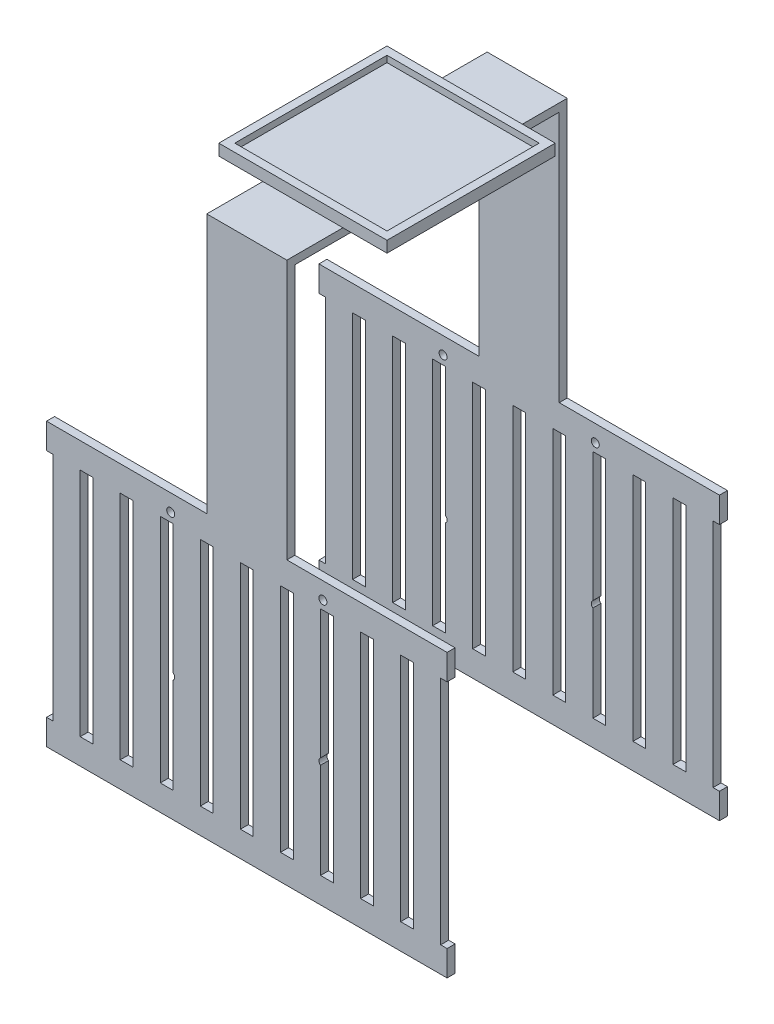
SolidWorks part; units mm, degrees
ref_plane "Plan de face" through (0, 0, 0) normal (0, 0, 1) x (1, 0, 0)
ref_plane "Plan de dessus" through (0, 0, 0) normal (0, 1, 0) x (1, 0, 0)
ref_plane "Plan de droite" through (0, 0, 0) normal (1, 0, 0) x (0, 0, -1)
sketch "Esquisse1" plane through (0, 0, 0) normal (0, 0, 1) x (1, 0, 0)
  line L0 (-62.5, 77.5) -> (62.5, 77.5) construction
  line L2 (-62.5, 88) -> (-62.5, -88)
  line L3 (-62.5, -88) -> (62.5, -88)
  line L4 (62.5, 88) -> (62.5, -88)
  line L5 (-62.5, 88) -> (62.5, -88) construction
  line L6 (-62.5, -88) -> (62.5, 88) construction
  line L7 (-62.5, -10.5) -> (62.5, -10.5) construction
  line L8 (0, 86.5) -> (0, -88) construction
  line L9 (-62.5, 88) -> (-25, 88)
  line L10 (-25, 88) -> (-25, 250.03)
  line L11 (-25, 250.03) -> (25, 250.03)
  line L12 (62.5, 88) -> (25, 88)
  line L13 (25, 88) -> (25, 250.03)
  circle A0 centre (-47.5, 77.5) radius 2.5
  circle A1 centre (-47.5, -10.5) radius 2.5
  circle A2 centre (47.5, -10.5) radius 2.5
  circle A3 centre (47.5, 77.5) radius 2.5
  point P0 (0, 0)
  point P28 (0, 250.03)
  dimension "D5" = 5
  dimension "D6" = 5
  dimension "D1" = 125
  dimension "D2" = 176
  dimension "D3" = 77.5
  dimension "D4" = 88
  dimension "D7" = 15
  dimension "D8" = 15
  dimension "D9" = 338.03
  dimension "D10" = 50
extrude "Boss.-Extru.1" add sketch "Esquisse1" along normal blind 5
sketch "Esquisse2" plane through (0, 250.03, 0) normal (0, 1, 0) x (1, 0, 0)
  line L1 (-25, -5) -> (25, -5)
  line L2 (-25, -5) -> (-25, 170)
  line L3 (-25, 170) -> (25, 170)
  line L4 (25, -5) -> (25, 170)
  dimension "D1" = 175
extrude "Boss.-Extru.2" add sketch "Esquisse2" against normal blind 5
sketch "Esquisse3" plane through (0, 0, -170) normal (0, 0, -1) x (-1, 0, 0)
  line L8 (25, 88) -> (25, 250.03)
  line L9 (25, 250.03) -> (-25, 250.03)
  line L10 (-25, 250.03) -> (-25, 88)
  line L11 (-25, 88) -> (-62.5, 88)
  line L12 (-62.5, 88) -> (-62.5, -88)
  line L13 (-62.5, -88) -> (62.5, -88)
  line L14 (62.5, -88) -> (62.5, 88)
  line L15 (62.5, 88) -> (25, 88)
  line L16 (25, 88) -> (25, 250.03)
  line L17 (25, 250.03) -> (-25, 250.03)
  line L18 (-25, 250.03) -> (-25, 88)
  line L19 (-25, 88) -> (-62.5, 88)
  line L20 (-62.5, 88) -> (-62.5, -88)
  line L21 (-62.5, -88) -> (62.5, -88)
  line L22 (62.5, -88) -> (62.5, 88)
  line L23 (62.5, 88) -> (25, 88)
  circle A1 centre (47.5, -10.5) radius 2.5
  circle A2 centre (47.5, -10.5) radius 2.5
  circle A3 centre (47.5, 77.5) radius 2.5
  circle A4 centre (47.5, 77.5) radius 2.5
  circle A5 centre (-47.5, 77.5) radius 2.5
  circle A6 centre (-47.5, 77.5) radius 2.5
  circle A7 centre (-47.5, -10.5) radius 2.5
  circle A8 centre (-47.5, -10.5) radius 2.5
  dimension "D1" = 0
  dimension "D2" = 0
  dimension "D3" = 0
  dimension "D4" = 0
  dimension "D5" = 0
extrude "Boss.-Extru.3" add sketch "Esquisse3" against normal blind 5
sketch "Esquisse4" plane through (0, 250.03, 0) normal (0, 1, 0) x (1, 0, 0)
  line L0 (-25, 82.5) -> (25, 82.5) construction
  line L1 (-25, -5) -> (-25, 170) construction
  line L2 (25, -5) -> (25, 170) construction
  line L3 (0, 170) -> (0, -5) construction
  line L4 (25, 170) -> (-25, 170) construction
  line L5 (25, -5) -> (-25, -5) construction
  line L7 (-52.5, 135) -> (52.5, 135)
  line L8 (-52.5, 135) -> (-52.5, 30)
  line L9 (-52.5, 30) -> (52.5, 30)
  line L10 (52.5, 135) -> (52.5, 30)
  line L11 (-52.5, 135) -> (52.5, 30) construction
  line L12 (-52.5, 30) -> (52.5, 135) construction
  point P12 (0, 82.5)
  dimension "D1" = 105
  dimension "D2" = 105
extrude "Boss.-Extru.4" add sketch "Esquisse4" along normal blind 3
sketch "Esquisse5" plane through (0, 253.03, 0) normal (0, 1, 0) x (1, 0, 0)
  line L0 (47.5, 130) -> (-47.5, 130)
  line L1 (-47.5, 130) -> (-47.5, 35)
  line L2 (-47.5, 35) -> (47.5, 35)
  line L3 (47.5, 35) -> (47.5, 130)
  line L4 (52.5, 30) -> (52.5, 135)
  line L5 (52.5, 135) -> (-52.5, 135)
  line L6 (-52.5, 135) -> (-52.5, 30)
  line L7 (-52.5, 30) -> (52.5, 30)
  line L8 (52.5, 30) -> (52.5, 135)
  line L9 (52.5, 135) -> (-52.5, 135)
  line L10 (-52.5, 135) -> (-52.5, 30)
  line L11 (-52.5, 30) -> (52.5, 30)
  dimension "D1" = 0
  dimension "D2" = 5
extrude "Boss.-Extru.5" add sketch "Esquisse5" along normal blind 4
sketch "Esquisse6" plane through (0, 0, -170) normal (0, 0, -1) x (-1, 0, 0)
  line L0 (-25, 88) -> (-62.5, 88) construction
  line L1 (-125, -88) -> (125, -88)
  line L2 (-125, -88) -> (-125, 88)
  line L3 (-125, 88) -> (125, 88)
  line L4 (125, -88) -> (125, 88)
  line L5 (-125, -88) -> (125, 88) construction
  line L6 (-125, 88) -> (125, -88) construction
  circle A0 centre (-47.5, 77.5) radius 2.5
  circle A1 centre (47.5, 77.5) radius 2.5023
  circle A2 centre (-47.5, -10.5) radius 2.6964
  circle A3 centre (47.5, -10.5) radius 2.6964
  point P0 (0, 0)
  dimension "D1" = 250
extrude "Boss.-Extru.6" add sketch "Esquisse6" against normal up to surface (5 mm away) up to face at (45, -10.5, -165)
sketch "Esquisse8" plane through (0, 0, 5) normal (0, 0, 1) x (1, 0, 0)
  line L4 (-125, -88) -> (125, -88)
  line L5 (-125, 88) -> (-125, -88)
  line L6 (125, 88) -> (-125, 88)
  line L7 (125, -88) -> (125, 88)
  line L8 (-125, -88) -> (125, -88)
  line L9 (-125, 88) -> (-125, -88)
  line L10 (125, 88) -> (-125, 88)
  line L11 (125, -88) -> (125, 88)
  circle A1 centre (47.5, -10.5) radius 2.6964
  circle A2 centre (47.5, -10.5) radius 2.6964
  circle A3 centre (-47.5, 77.5) radius 2.5023
  circle A4 centre (-47.5, 77.5) radius 2.5023
  circle A5 centre (47.5, 77.5) radius 2.5
  circle A6 centre (47.5, 77.5) radius 2.5
  circle A7 centre (-47.5, -10.5) radius 2.6964
  circle A8 centre (-47.5, -10.5) radius 2.6964
  dimension "D1" = 0
  dimension "D2" = 0
  dimension "D3" = 0
  dimension "D4" = 0
  dimension "D5" = 0
extrude "Boss.-Extru.7" add sketch "Esquisse8" against normal up to surface (5 mm away) up to face at (0, 83.2575, 0)
sketch "Esquisse9" plane through (0, 0, -170) normal (0, 0, -1) x (-1, 0, 0)
  line L1 (-4, 72.0702) -> (4, 72.0702)
  line L2 (-4, 72.0702) -> (-4, -72.0702)
  line L3 (-4, -72.0702) -> (4, -72.0702)
  line L4 (4, 72.0702) -> (4, -72.0702)
  line L5 (-4, 72.0702) -> (4, -72.0702) construction
  line L6 (-4, -72.0702) -> (4, 72.0702) construction
  point P0 (0, 0)
  dimension "D1" = 8
extrude "Enlèv. mat.-Extru.1" cut sketch "Esquisse9" against normal blind 296
pattern_linear "Répétition linéaire1" count 6 spacing 25 along (-1, 0, 0) count 6 spacing 25 along (1, 0, 0) of "Enlèv. mat.-Extru.1"
